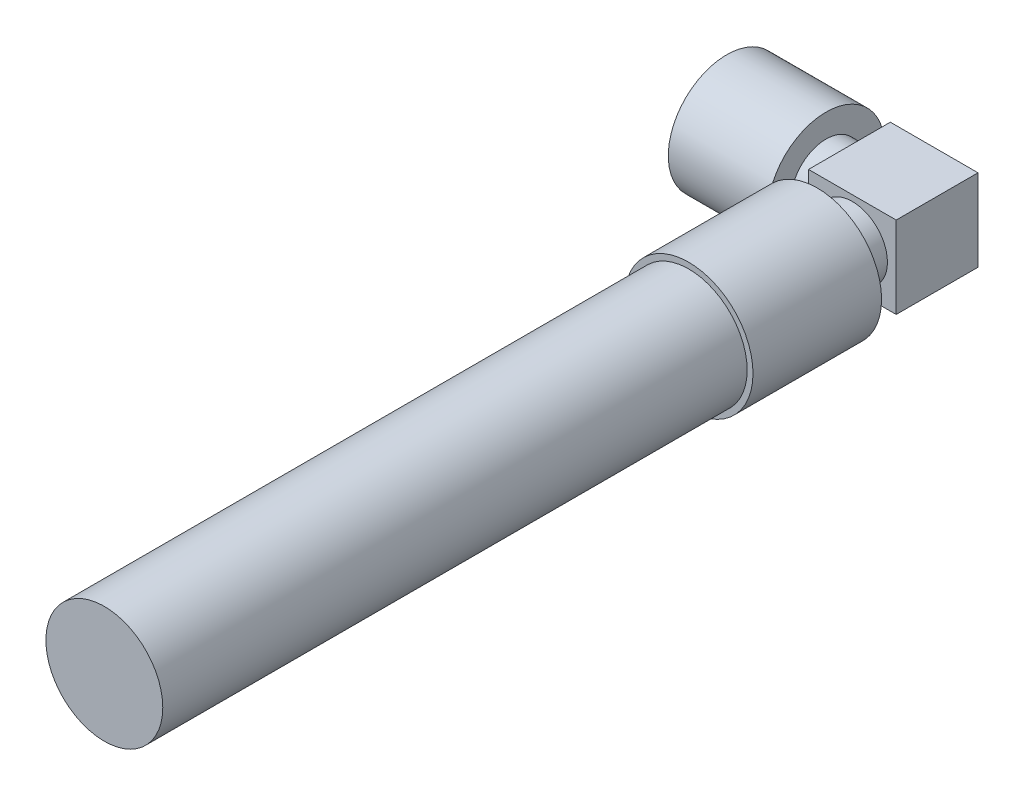
SolidWorks part; units mm, degrees
ref_plane "Front Plane" through (0, 0, 0) normal (0, 0, 1) x (1, 0, 0)
ref_plane "Top Plane" through (0, 0, 0) normal (0, 1, 0) x (1, 0, 0)
ref_plane "Right Plane" through (0, 0, 0) normal (1, 0, 0) x (0, 0, -1)
sketch "Sketch1" plane through (0, 0, 0) normal (1, 0, 0) x (0, 0, -1)
  circle A0 centre (0, 0) radius 5
  dimension "D1" = 10
extrude "Barrel Connector" add sketch "Sketch1" against normal blind 8.5
sketch "Sketch2" plane through (0, 0, 0) normal (1, 0, 0) x (0, 0, -1)
  circle A0 centre (0, 0) radius 3
  dimension "D1" = 6
extrude "Boss-Extrude2" add sketch "Sketch2" along normal blind 2
sketch "Sketch3" plane through (2, 0, 0) normal (1, 0, 0) x (0, 0, -1)
  line L1 (-3.5, 3.5) -> (3.5, 3.5)
  line L2 (-3.5, 3.5) -> (-3.5, -3.5)
  line L3 (-3.5, -3.5) -> (3.5, -3.5)
  line L4 (3.5, 3.5) -> (3.5, -3.5)
  line L5 (-3.5, 3.5) -> (3.5, -3.5) construction
  line L6 (-3.5, -3.5) -> (3.5, 3.5) construction
  point P0 (0, 0)
  dimension "D1" = 7
extrude "Boss-Extrude3" add sketch "Sketch3" along normal blind 7.5
sketch "Sketch4" plane through (0, 0, 3.5) normal (0, 0, 1) x (1, 0, 0)
  line L0 (2, 3.5) -> (9.5, -3.5) construction
  circle A0 centre (5.75, 0) radius 3
  point P7 (5.75, 0)
  dimension "D1" = 6
extrude "Boss-Extrude4" add sketch "Sketch4" along normal blind 3
sketch "Sketch5" plane through (0, 0, 6.5) normal (0, 0, 1) x (1, 0, 0)
  circle A0 centre (5.75, 0) radius 5.5
  circle A1 centre (5.75, 0) radius 3 construction
  dimension "D1" = 11
extrude "Boss-Extrude5" add sketch "Sketch5" along normal blind 11
sketch "Sketch6" plane through (0, 0, 17.5) normal (0, 0, 1) x (1, 0, 0)
  circle A0 centre (5.75, 0) radius 5
  circle A1 centre (5.75, 0) radius 5.5 construction
  dimension "D1" = 10
extrude "Boss-Extrude6" add sketch "Sketch6" along normal blind 50
